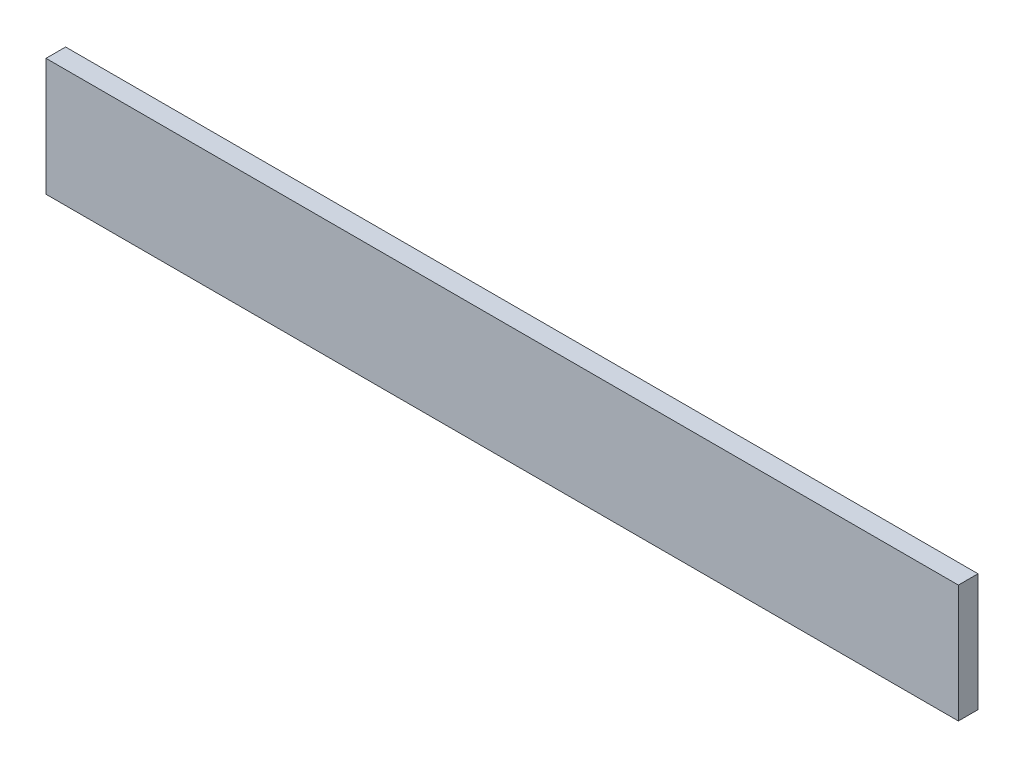
SolidWorks part; units mm, degrees
ref_plane "Ön Düzlem" through (0, 0, 0) normal (0, 0, 1) x (1, 0, 0)
ref_plane "Üst Düzlem" through (0, 0, 0) normal (0, 1, 0) x (1, 0, 0)
ref_plane "Sağ Düzlem" through (0, 0, 0) normal (1, 0, 0) x (0, 0, -1)
sketch "Çizim2" plane through (0, 0, 0) normal (0, 0, 1) x (1, 0, 0)
  line L0 (0, 151.9181) -> (0, -166.3966) construction
  line L1 (-176.0984, 0) -> (194.5898, 0) construction
  line L2 (-232.5, 80.9228) -> (232.5, 80.9228)
  line L3 (-232.5, 20.9228) -> (-232.5, 80.9228)
  line L4 (232.5, 20.9228) -> (-232.5, 20.9228)
  line L5 (232.5, 80.9228) -> (232.5, 20.9228)
  dimension "D1" = 465
  dimension "D2" = 60
extrude "Yükseklik-Ekstrüzyon1" add sketch "Çizim2" along normal blind 10 contours L2 L5 L4 L3
